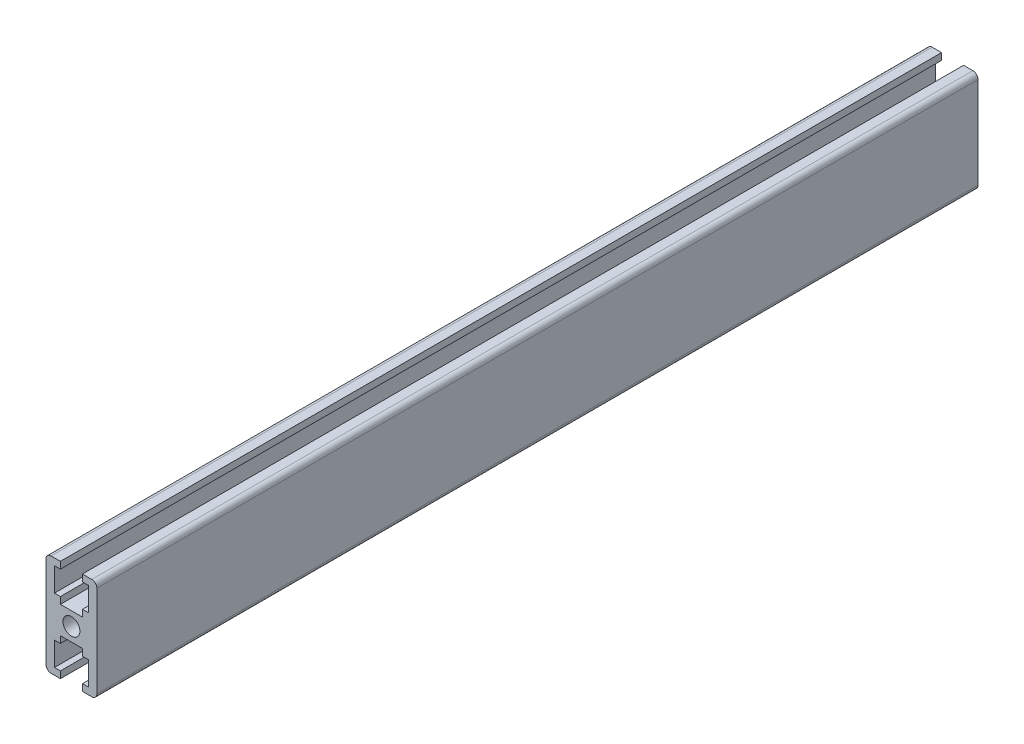
SolidWorks part; units mm, degrees
ref_plane "Plane1" through (0, 0, 0) normal (0, 0, 1) x (1, 0, 0)
ref_plane "Plane2" through (0, 0, 0) normal (0, 1, 0) x (1, 0, 0)
ref_plane "Plane3" through (0, 0, 0) normal (1, 0, 0) x (0, 0, -1)
sketch "Sketch1" plane through (0, 0, 0) normal (0, 0, 1) x (1, 0, 0)
  line L1 (0, 16.311) -> (0, -16.311) construction
  line L2 (0, 0) -> (9.513, 0) construction
  line L3 (-6, -15) -> (-3.25, -15)
  line L4 (-7.5, -13.5) -> (-7.5, 13.5)
  line L5 (-6, 15) -> (-3.25, 15)
  line L6 (7.5, -13.5) -> (7.5, 13.5)
  line L8 (-3.25, 4) -> (3.25, 4)
  line L17 (3.25, 15) -> (6, 15)
  line L18 (-3.25, 6) -> (-3.25, 4)
  line L19 (-5, 6) -> (-3.25, 6)
  line L20 (-5, 13) -> (-5, 6)
  line L21 (-3.25, 13) -> (-5, 13)
  line L22 (3.25, 6) -> (3.25, 4)
  line L23 (5, 6) -> (3.25, 6)
  line L24 (5, 13) -> (5, 6)
  line L25 (3.25, 13) -> (5, 13)
  line L26 (-3.25, 15) -> (-3.25, 13)
  line L27 (3.25, 15) -> (3.25, 13)
  line L38 (3.25, -6) -> (3.25, -4)
  line L39 (5, -6) -> (3.25, -6)
  line L40 (5, -13) -> (5, -6)
  line L41 (3.25, -13) -> (5, -13)
  line L42 (-3.25, -6) -> (-3.25, -4)
  line L43 (-5, -6) -> (-3.25, -6)
  line L44 (-5, -13) -> (-5, -6)
  line L45 (-3.25, -13) -> (-5, -13)
  line L46 (-3.25, -4) -> (3.25, -4)
  line L47 (3.25, -15) -> (3.25, -13)
  line L48 (-3.25, -15) -> (-3.25, -13)
  line L49 (3.25, -15) -> (6, -15)
  arc A0 (-6, -15) -> (-7.5, -13.5) centre (-6, -13.5) cw
  arc A1 (6, -15) -> (7.5, -13.5) centre (6, -13.5) ccw
  arc A2 (6, 15) -> (7.5, 13.5) centre (6, 13.5) cw
  arc A3 (-7.5, 13.5) -> (-6, 15) centre (-6, 13.5) cw
  circle A4 centre (0, 0) radius 2.5
  point P4 (0, 0)
  point P44 (-7.5, 15)
  point P45 (7.5, 15)
  point P46 (7.5, -15)
  point P47 (-7.5, -15)
  point P48 (0, -15)
  point P49 (0, 15)
extrude "凸台-拉伸1" add sketch "Sketch1" along normal blind 260
hole_wizard "M6 螺纹孔1" positions "草图2" profile "草图1" tap size "M6" standard "Gb"
sketch "草图2" plane through (0, 0, 260) normal (0, 0, 1) x (1, 0, 0)
  line L2 (-7.5, 13.5) -> (-7.5, -13.5) construction
  line L6 (-3.25, 15) -> (-6, 15) construction
  point P0 (0, 0)
  point P11 (-4.316, 15)
  dimension "D1" = 7.5
  dimension "D2" = 15
sketch "草图1" plane through (0, 0, 260) normal (1, 0, 0) x (0, -1, 0)
  line L0 (0, 0) -> (0, 21.5022)
  line L1 (0, 21.5022) -> (2.5, 20)
  line L2 (2.5, 20) -> (2.5, 0)
  line L5 (2.5, 0) -> (0, 0)
  line L10 (0, 21.5022) -> (-2.5, 20) construction
  line L11 (0, -6.35) -> (0, 107.95) construction
  dimension "螺纹孔钻头直径" = 5
  dimension "螺纹孔钻头深度" = 20
  dimension "导头角度" = 118
hole_wizard "M6 螺纹孔2" positions "草图4" profile "草图3" tap size "M6" standard "Gb"
sketch "草图4" plane through (0, 0, 0) normal (0, 0, -1) x (-1, 0, 0)
  line L0 (-7.5, -13.5) -> (-7.5, 13.5) construction
  line L1 (-3.25, -15) -> (-6, -15) construction
  point P0 (0, 0)
  dimension "D1" = 7.5
  dimension "D2" = 15
sketch "草图3" plane through (0, 0, 0) normal (1, 0, 0) x (0, 1, 0)
  line L0 (0, 0) -> (0, 21.5022)
  line L1 (0, 21.5022) -> (2.5, 20)
  line L2 (2.5, 20) -> (2.5, 0)
  line L5 (2.5, 0) -> (0, 0)
  line L10 (0, 21.5022) -> (-2.5, 20) construction
  line L11 (0, -6.35) -> (0, 107.95) construction
  dimension "螺纹孔钻头直径" = 5
  dimension "螺纹孔钻头深度" = 20
  dimension "导头角度" = 118
